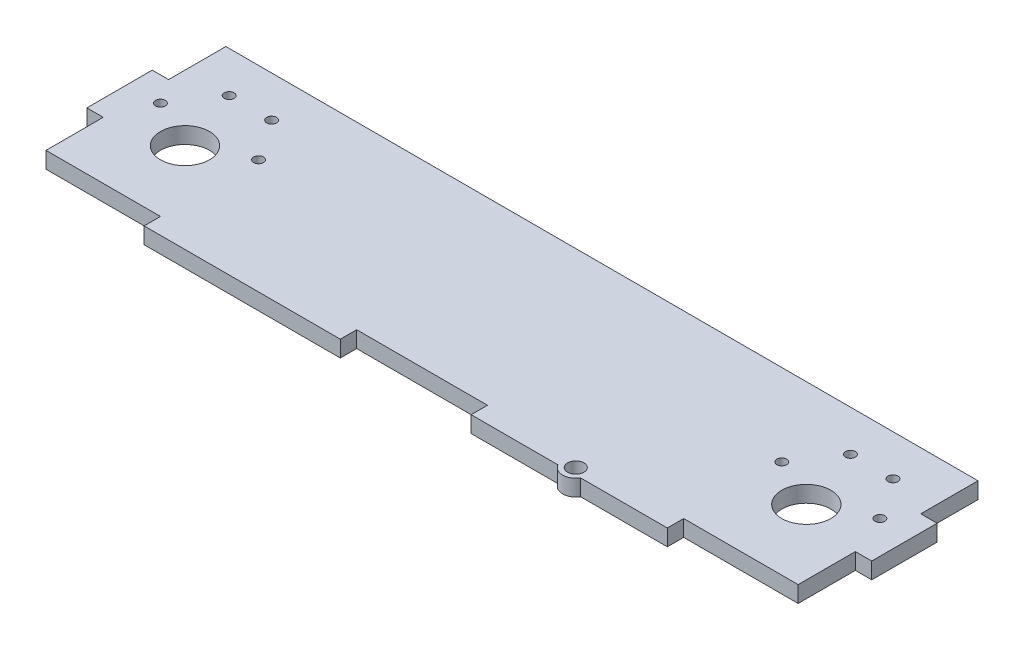
SolidWorks part; units mm, degrees
ref_plane "Plan de face" through (0, 0, 0) normal (0, 0, 1) x (1, 0, 0)
ref_plane "Plan de dessus" through (0, 0, 0) normal (0, 1, 0) x (1, 0, 0)
ref_plane "Plan de droite" through (0, 0, 0) normal (1, 0, 0) x (0, 0, -1)
sketch "Esquisse2" plane through (0, 0, 0) normal (0, 1, 0) x (1, 0, 0)
  line L0 (-75.2145, -31.3914) -> (-75.2145, -26.3914)
  line L1 (-110.2145, 28.6086) -> (119.7855, 28.6086)
  line L2 (-115.2145, 11.1086) -> (-115.2145, -8.8914)
  line L3 (-75.2145, -31.3914) -> (-15.2145, -31.3914)
  line L4 (124.7855, 11.1086) -> (124.7855, -8.8914)
  line L7 (-75.2145, -26.3914) -> (-110.2145, -26.3914)
  line L8 (-15.2145, -31.3914) -> (-15.2145, -26.3914)
  line L9 (-15.2145, -26.3914) -> (24.7855, -26.3914)
  line L10 (24.7855, -26.3914) -> (24.7855, -31.3914)
  line L11 (84.7855, -31.3914) -> (84.7855, -26.3914)
  line L12 (84.7855, -26.3914) -> (119.7855, -26.3914)
  line L13 (24.7855, -31.3914) -> (84.7855, -31.3914)
  line L14 (99.7855, -3.8914) -> (99.7855, 22.877) construction
  line L15 (114.7855, 20.1843) -> (114.7855, -1.3914) construction
  line L16 (99.7855, 3.6086) -> (129.7855, 3.6086) construction
  line L17 (106.2855, 24.9898) -> (106.2855, 7.2273) construction
  line L18 (4.7855, 28.6086) -> (4.7855, -24.6414) construction
  line L19 (124.7855, -8.8914) -> (119.7855, -8.8914)
  line L20 (-110.2145, 11.1086) -> (-110.2145, 28.6086)
  line L21 (119.7855, 11.1086) -> (124.7855, 11.1086)
  line L22 (119.7855, -8.8914) -> (119.7855, -26.3914)
  line L23 (119.7855, 11.1086) -> (119.7855, 28.6086)
  line L24 (-110.2145, -8.8914) -> (-110.2145, -26.3914)
  line L25 (-110.2145, 11.1086) -> (-115.2145, 11.1086)
  line L26 (-115.2145, -8.8914) -> (-110.2145, -8.8914)
  line L27 (-115.1149, -26.3914) -> (-115.2145, -26.3914)
  circle A0 centre (99.7855, -3.8914) radius 7.5
  circle A1 centre (114.7855, 3.6086) radius 1.5
  circle A2 centre (106.2855, 16.1086) radius 1.5
  circle A3 centre (93.2855, 16.1086) radius 1.5
  circle A4 centre (84.7855, 3.6086) radius 1.5
  circle A5 centre (54.7855, -29.3914) radius 4
  circle A6 centre (54.7855, -29.3914) radius 2.5
  circle A9 centre (-105.2145, 3.6086) radius 1.5
  circle A10 centre (-96.7145, 16.1086) radius 1.5
  circle A11 centre (-83.7145, 16.1086) radius 1.5
  circle A12 centre (-75.2145, 3.6086) radius 1.5
  circle A13 centre (-90.2145, -3.8914) radius 7.5
  point P0 (0, 0)
  dimension "D7" = 15
  dimension "D9" = 15
  dimension "D10" = 3
  dimension "D11" = 3
  dimension "D15" = 2
  dimension "D16" = 5
  dimension "D17" = 8
  dimension "D18" = 20
  dimension "D2" = 5
  dimension "D3" = 35
  dimension "D4" = 40
  dimension "D5" = 60
  dimension "D6" = 60
  dimension "D8" = 22.5
  dimension "D12" = 12.5
  dimension "D13" = 6.5
  dimension "D14" = 25
  dimension "D19" = 17.5
  dimension "D20" = 17.5
  dimension "D21" = 35
  dimension "D22" = 5
  dimension "D23" = 5
  dimension "D24" = 30
extrude "Boss.-Extru.5" add sketch "Esquisse2" along normal blind 5 contours A5 L13 L11 L12 L22 L19 L4 L21 L23 L1 L20 L25 L2 L26 L24 L7 L0 L3 L8 L9 L10 A10 A4 A0 A1 A2 A3 A9 A11 A12 A13 | A6 L13 A5 | A6 L13 A5
